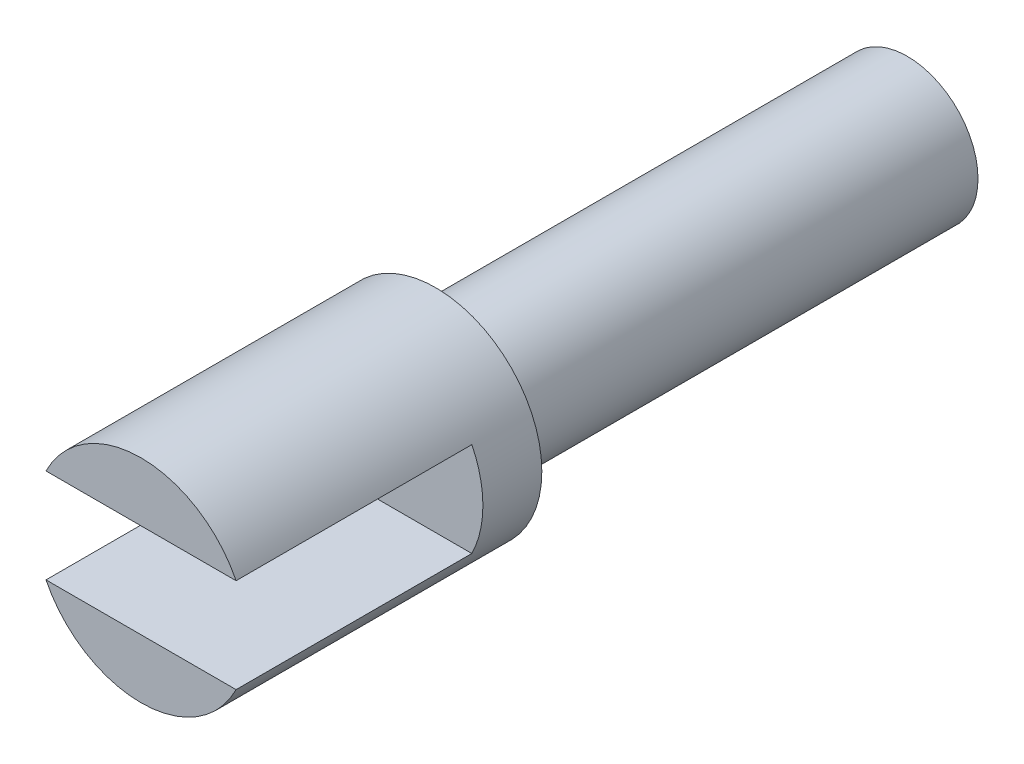
SolidWorks part; units mm, degrees
material "1.0545 (S355N)"
ref_plane "Płaszczyzna przednia" through (0, 0, 0) normal (0, 0, 1) x (1, 0, 0)
ref_plane "Płaszczyzna górna" through (0, 0, 0) normal (0, 1, 0) x (1, 0, 0)
ref_plane "Płaszczyzna prawa" through (0, 0, 0) normal (1, 0, 0) x (0, 0, -1)
sketch "Szkic1" plane through (0, 0, 0) normal (0, 1, 0) x (1, 0, 0)
  line L0 (0, -44.41) -> (0, 49.6533) construction
  line L1 (-9, 0) -> (9, 0)
  line L2 (-9, 0) -> (-9, -25)
  line L3 (-9, -25) -> (9, -25)
  line L4 (9, 0) -> (9, -25)
  line L5 (-6, 40) -> (6, 40)
  line L6 (-6, 40) -> (-6, 0)
  line L7 (-6, 0) -> (6, 0)
  line L8 (6, 40) -> (6, 0)
  point P8 (0, 0)
  point P9 (0, 0)
  dimension "D1" = 12
  dimension "D2" = 18
  dimension "D3" = 40
  dimension "D4" = 25
revolve "Obrót1" add sketch "Szkic1" angle 360 about L0
sketch "Szkic2" plane through (0, 0, 25) normal (0, 0, 1) x (1, 0, 0)
  line L1 (-9, 4) -> (9, 4)
  line L2 (-9, 4) -> (-9, -4)
  line L3 (-9, -4) -> (9, -4)
  line L4 (9, 4) -> (9, -4)
  circle A2 centre (0, 0) radius 9 construction
  point P4 (0, 4)
  point P6 (-9, 0)
  point P7 (9, 0)
  dimension "D1" = 8
extrude "Wytnij-wyciągnięcie1" cut sketch "Szkic2" against normal blind 20
equation "\"D1@Wytnij-wyciągnięcie1\"=\"D4@Szkic1\" - 5"
